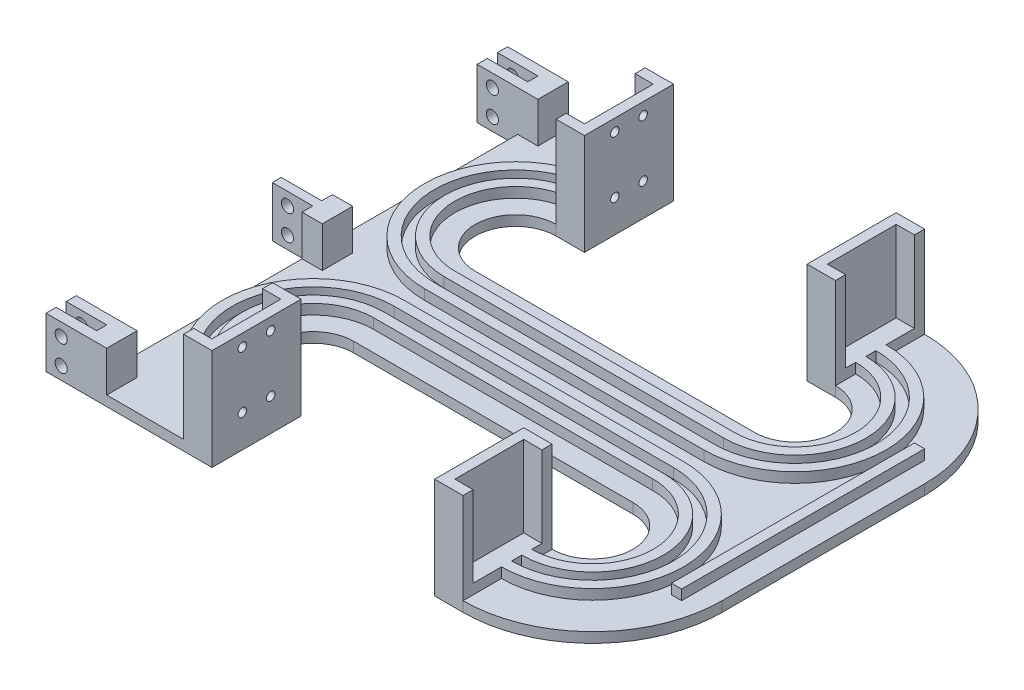
SolidWorks part; units mm, degrees
ref_plane "Front Plane" through (0, 0, 0) normal (0, 0, 1) x (1, 0, 0)
ref_plane "Top Plane" through (0, 0, 0) normal (0, 1, 0) x (1, 0, 0)
ref_plane "Right Plane" through (0, 0, 0) normal (1, 0, 0) x (0, 0, -1)
sketch "Sketch2" plane through (0, 0, 0) normal (0, 1, 0) x (1, 0, 0)
  line L0 (62.5, 25) -> (62.5, -25)
  line L1 (23.5, -35) -> (30.5, -35)
  line L2 (23.5, -57) -> (30.5, -57)
  line L3 (30.5, -15) -> (-38.5, -15)
  line L4 (-62.5, 0) -> (62.5, 0) construction
  line L5 (30.5, 57) -> (30.5, -57) construction
  line L6 (23.5, -35) -> (23.5, -57)
  line L7 (-31.5, -35) -> (-38.5, -35)
  line L8 (-31.5, -57) -> (-38.5, -57)
  line L9 (-38.5, -57) -> (-38.5, 57) construction
  line L10 (62.5, -25) -> (-62.5, -25) construction
  line L11 (-38.5, -57) -> (-62.5, -57)
  line L12 (-31.5, -35) -> (-31.5, -57)
  line L13 (-62.5, -57) -> (-62.5, 57)
  line L14 (62.5, 25) -> (-62.5, 25) construction
  line L15 (-31.5, 35) -> (-31.5, 57)
  line L16 (-38.5, 57) -> (-62.5, 57)
  line L17 (-31.5, 57) -> (-38.5, 57)
  line L18 (-31.5, 35) -> (-38.5, 35)
  line L19 (23.5, 35) -> (23.5, 57)
  line L20 (30.5, 15) -> (-38.5, 15)
  line L21 (23.5, 57) -> (30.5, 57)
  line L22 (23.5, 35) -> (30.5, 35)
  arc A0 (62.5, -25) -> (30.5, -57) centre (30.5, -25) cw
  arc A1 (30.5, -35) -> (30.5, -15) centre (30.5, -25) ccw
  arc A2 (-38.5, -15) -> (-38.5, -35) centre (-38.5, -25) ccw
  arc A3 (-38.5, 15) -> (-38.5, 35) centre (-38.5, 25) cw
  arc A4 (30.5, 35) -> (30.5, 15) centre (30.5, 25) cw
  arc A5 (62.5, 25) -> (30.5, 57) centre (30.5, 25) ccw
  point P33 (-38.5, 0)
  point P34 (30.5, 0)
  point P45 (0, 0)
  dimension "D2" = 10
  dimension "D1" = 25
  dimension "D3" = 125
  dimension "D4" = 55
  dimension "D5" = 22
  dimension "D6" = 7
extrude "Boss-Extrude1" add sketch "Sketch2" along normal blind 2.5
sketch "Sketch3" plane through (0, 2.5, 0) normal (0, 1, 0) x (1, 0, 0)
  line L0 (30.5, -40.0006) -> (30.5, -35)
  line L1 (30.3681, -7.5) -> (-38.6319, -7.5)
  line L3 (30.3681, -10) -> (-38.6319, -10)
  line L5 (0, 0) -> (62.5, 0) construction
  line L6 (62.5, -25) -> (62.5, 25) construction
  line L7 (-38.5, -15) -> (30.5, -15) construction
  line L8 (30.5, -2.5) -> (-38.5, -2.5)
  line L10 (30.5, -5) -> (-38.5, -5)
  line L12 (-38.5, -40.0006) -> (-38.5, -35)
  line L13 (-38.5, -35) -> (-31.5, -35)
  line L14 (-31.5, -35) -> (-31.5, -57)
  line L15 (-31.5, -57) -> (-38.5, -57)
  line L16 (-62.5, -57) -> (-31.5, -57) construction
  line L17 (-38.5, -57) -> (-38.5, -47.5)
  line L18 (-38.5, -42.5005) -> (-38.5, -45)
  line L19 (30.5, -35) -> (23.5, -35)
  line L20 (23.5, -35) -> (23.5, -57)
  line L21 (23.5, -57) -> (30.5, -57)
  line L22 (30.5, -57) -> (30.5, -47.5)
  line L23 (30.5, -42.5005) -> (30.5, -45)
  line L24 (30.5, 42.5005) -> (30.5, 45)
  line L25 (30.5, 57) -> (30.5, 47.5)
  line L26 (23.5, 57) -> (30.5, 57)
  line L27 (23.5, 35) -> (23.5, 57)
  line L28 (30.5, 35) -> (23.5, 35)
  line L29 (-38.5, 42.5005) -> (-38.5, 45)
  line L30 (-38.5, 57) -> (-38.5, 47.5)
  line L31 (-31.5, 57) -> (-38.5, 57)
  line L32 (-31.5, 35) -> (-31.5, 57)
  line L33 (-38.5, 35) -> (-31.5, 35)
  line L34 (-38.5, 40.0006) -> (-38.5, 35)
  line L35 (30.5, 5) -> (-38.5, 5)
  line L36 (30.5, 2.5) -> (-38.5, 2.5)
  line L37 (30.3681, 10) -> (-38.6319, 10)
  line L38 (30.3681, 7.5) -> (-38.6319, 7.5)
  line L39 (30.5, 40.0006) -> (30.5, 35)
  line L40 (57.5, 30) -> (55, 30)
  line L42 (57.5, 30) -> (57.5, -30)
  line L43 (57.5, -30) -> (55, -30)
  line L44 (55, 30) -> (55, -30)
  arc A0 (-38.6319, -10) -> (-38.5, -40.0006) centre (-38.5, -25) ccw
  arc A1 (-38.6319, -7.5) -> (-38.5, -42.5005) centre (-38.5, -25) ccw
  arc A2 (-38.5, -5) -> (-38.5, -45) centre (-38.5, -25) ccw
  arc A3 (-38.5, -2.5) -> (-38.5, -47.5) centre (-38.5, -25) ccw
  arc A4 (30.3681, -10) -> (30.5, -40.0006) centre (30.5, -25) cw
  arc A5 (30.3681, -7.5) -> (30.5, -42.5005) centre (30.5, -25) cw
  arc A6 (30.5, -5) -> (30.5, -45) centre (30.5, -25) cw
  arc A7 (30.5, -2.5) -> (30.5, -47.5) centre (30.5, -25) cw
  arc A8 (30.5, 2.5) -> (30.5, 47.5) centre (30.5, 25) ccw
  arc A9 (30.5, 5) -> (30.5, 45) centre (30.5, 25) ccw
  arc A10 (30.3681, 7.5) -> (30.5, 42.5005) centre (30.5, 25) ccw
  arc A11 (30.3681, 10) -> (30.5, 40.0006) centre (30.5, 25) ccw
  arc A12 (-38.5, 2.5) -> (-38.5, 47.5) centre (-38.5, 25) cw
  arc A13 (-38.5, 5) -> (-38.5, 45) centre (-38.5, 25) cw
  arc A14 (-38.6319, 7.5) -> (-38.5, 42.5005) centre (-38.5, 25) cw
  arc A15 (-38.6319, 10) -> (-38.5, 40.0006) centre (-38.5, 25) cw
  point P49 (55, 0)
  point P50 (57.5, 0)
  point P53 (-38.5, -43.7502)
  point P54 (30.5, -43.7502)
  dimension "D5" = 22.5
  dimension "D6" = 20
  dimension "D7" = 17.5005
  dimension "D1" = 2.5
  dimension "D2" = 2.5
  dimension "D3" = 5
  dimension "D4" = 2.5
  dimension "D8" = 2.5
  dimension "D9" = 30
  dimension "D10" = 5
extrude "Boss-Extrude4" add sketch "Sketch3" along normal blind 2.5
sketch "Sketch6" plane through (0, 5, 0) normal (0, 1, 0) x (1, 0, 0)
  line L0 (-38.5, -35) -> (-31.5, -35)
  line L1 (-31.5, -35) -> (-31.5, -57)
  line L2 (-31.5, -57) -> (-38.5, -57)
  line L3 (-38.5, -57) -> (-38.5, -54.5)
  line L4 (-38.5, -47.5) -> (-38.5, -57) construction
  line L5 (-38.5, -54.5) -> (-34, -54.5)
  line L6 (-34, -54.5) -> (-34, -37.5)
  line L7 (-34, -37.5) -> (-38.5, -37.5)
  line L8 (-38.5, -35) -> (-38.5, -40.0006) construction
  line L9 (-38.5, -37.5) -> (-38.5, -35)
  line L11 (30.5, -35) -> (23.5, -35)
  line L12 (23.5, -35) -> (23.5, -57)
  line L13 (23.5, -57) -> (30.5, -57)
  line L14 (30.5, -57) -> (30.5, -54.5)
  line L15 (30.5, -57) -> (30.5, -47.5) construction
  line L16 (30.5, -54.5) -> (26, -54.5)
  line L17 (26, -54.5) -> (26, -37.5)
  line L18 (26, -37.5) -> (30.5, -37.5)
  line L19 (30.5, -40.0006) -> (30.5, -35) construction
  line L20 (30.5, -37.5) -> (30.5, -35)
  line L21 (-1.375, 0) -> (1.375, 0) construction
  line L22 (30.5, 37.5) -> (30.5, 35)
  line L23 (26, 37.5) -> (30.5, 37.5)
  line L24 (26, 54.5) -> (26, 37.5)
  line L25 (30.5, 54.5) -> (26, 54.5)
  line L26 (30.5, 57) -> (30.5, 54.5)
  line L27 (23.5, 57) -> (30.5, 57)
  line L28 (23.5, 35) -> (23.5, 57)
  line L29 (30.5, 35) -> (23.5, 35)
  line L30 (-38.5, 37.5) -> (-38.5, 35)
  line L31 (-34, 37.5) -> (-38.5, 37.5)
  line L32 (-34, 54.5) -> (-34, 37.5)
  line L33 (-38.5, 54.5) -> (-34, 54.5)
  line L34 (-38.5, 57) -> (-38.5, 54.5)
  line L35 (-31.5, 57) -> (-38.5, 57)
  line L36 (-31.5, 35) -> (-31.5, 57)
  line L37 (-38.5, 35) -> (-31.5, 35)
  dimension "D1" = 2.5
  dimension "D2" = 2.5
  dimension "D3" = 2.5
extrude "Boss-Extrude5" add sketch "Sketch6" along normal blind 20
sketch "Sketch7" plane through (23.5, 0, 0) normal (-1, 0, 0) x (0, 0, 1)
  line L0 (37.5, 25) -> (54.5, 25) construction
  line L1 (57, 25) -> (57, 2.5) construction
  circle A0 centre (46, 13.75) radius 3.75
  point P4 (46, 25)
  point P7 (57, 13.75)
  dimension "D1" = 7.5
extrude "Boss-Extrude6" add sketch "Sketch7" along normal blind 5.5 contours A0
sketch "Sketch9" plane through (23.5, 0, 0) normal (-1, 0, 0) x (0, 0, 1)
  line L0 (-54.5, 25) -> (-37.5, 25) construction
  line L1 (-57, 25) -> (-57, 2.5) construction
  circle A0 centre (-46, 13.75) radius 3.75
  point P5 (-46, 25)
  point P8 (-57, 13.75)
  dimension "D1" = 7.5
extrude "Boss-Extrude7" add sketch "Sketch9" along normal blind 5.5
sketch "Sketch10" plane through (-31.5, 0, 0) normal (1, 0, 0) x (0, 0, -1)
  line L0 (-57, 12.5) -> (-35, 12.5) construction
  line L1 (-57, 25) -> (-57, 0) construction
  line L2 (-35, 25) -> (-35, 0) construction
  line L3 (-46, 25) -> (-46, 0) construction
  line L4 (-57, 25) -> (-35, 25) construction
  line L5 (-57, 0) -> (-35, 0) construction
  line L6 (-57, 15) -> (-35, 15) construction
  circle A0 centre (-42.5, 22) radius 1.05
  circle A1 centre (-49.5, 22) radius 1.05
  circle A4 centre (-49.5, 8) radius 1.05
  circle A5 centre (-42.5, 8) radius 1.05
  dimension "D3" = 2.1
  dimension "D1" = 2.5
  dimension "D2" = 3.5
  dimension "D4" = 7
extrude "Cut-Extrude1" cut sketch "Sketch10" against normal blind 2.5
sketch "Sketch12" plane through (-31.5, 0, 0) normal (1, 0, 0) x (0, 0, -1)
  line L0 (46, 25) -> (46, 0) construction
  line L1 (35, 25) -> (57, 25) construction
  line L2 (35, 0) -> (57, 0) construction
  line L3 (57, 12.5) -> (35, 12.5) construction
  line L4 (57, 25) -> (57, 0) construction
  line L5 (35, 25) -> (35, 0) construction
  line L6 (35, 15) -> (57, 15) construction
  circle A0 centre (49.5, 22) radius 1.05
  circle A1 centre (42.5, 22) radius 1.05
  circle A2 centre (42.5, 8) radius 1.05
  circle A3 centre (49.5, 8) radius 1.05
  dimension "D4" = 2.1
  dimension "D1" = 2.5
  dimension "D2" = 7
  dimension "D3" = 3.5
extrude "Cut-Extrude2" cut sketch "Sketch12" against normal blind 2.5
sketch "Sketch14" plane through (0, 2.5, 0) normal (0, 1, 0) x (1, 0, 0)
  line L0 (-62.5, 57) -> (-62.5, -57) construction
  line L1 (-62.5, 3.75) -> (-57.5, 3.75)
  line L2 (-62.5, 3.75) -> (-62.5, -3.75)
  line L3 (-62.5, -3.75) -> (-57.5, -3.75)
  line L4 (-57.5, 3.75) -> (-57.5, -3.75)
  line L6 (-62.5, -57) -> (-57.5, -57)
  line L7 (-62.5, -57) -> (-62.5, -49.5)
  line L8 (-62.5, -49.5) -> (-57.5, -49.5)
  line L9 (-57.5, -57) -> (-57.5, -49.5)
  line L10 (-62.5, 57) -> (-57.5, 57)
  line L11 (-62.5, 57) -> (-62.5, 49.5)
  line L12 (-62.5, 49.5) -> (-57.5, 49.5)
  line L13 (-57.5, 57) -> (-57.5, 49.5)
  point P6 (-57.5, 0)
  dimension "D1" = 7.5
  dimension "D2" = 5
  dimension "D3" = 7.5
extrude "Boss-Extrude8" add sketch "Sketch14" along normal blind 10
sketch "Sketch15" plane through (-62.5, 0, 0) normal (-1, 0, 0) x (0, 0, 1)
  line L0 (-57, 0) -> (57, 0) construction
  line L5 (-1.1, 12.5) -> (1.1, 12.5)
  line L6 (57, 12.5) -> (54.5, 12.5)
  line L7 (57, 12.5) -> (57, 0)
  line L8 (57, 0) -> (54.5, 0)
  line L9 (54.5, 12.5) -> (54.5, 0)
  line L10 (49.5, 12.5) -> (52, 12.5)
  line L11 (49.5, 12.5) -> (49.5, 0)
  line L12 (49.5, 0) -> (52, 0)
  line L13 (52, 12.5) -> (52, 0)
  line L27 (-3.75, 12.5) -> (3.75, 12.5) construction
  line L28 (1.1, 12.5) -> (1.1, 0)
  line L29 (1.1, 0) -> (-1.1, 0)
  line L31 (0, 12.5) -> (0, 0) construction
  line L32 (-1.1, 12.5) -> (-1.1, 0)
  line L33 (-52, 12.5) -> (-52, 0)
  line L34 (-49.5, 0) -> (-52, 0)
  line L35 (-49.5, 12.5) -> (-49.5, 0)
  line L36 (-49.5, 12.5) -> (-52, 12.5)
  line L37 (-54.5, 12.5) -> (-54.5, 0)
  line L38 (-57, 0) -> (-54.5, 0)
  line L39 (-57, 12.5) -> (-57, 0)
  line L40 (-57, 12.5) -> (-54.5, 12.5)
  dimension "D1" = 1.1
extrude "Boss-Extrude9" add sketch "Sketch15" along normal blind 10
sketch "Sketch16" plane through (0, 0, 57) normal (0, 0, 1) x (1, 0, 0)
  line L0 (-65, 12.5) -> (-65, 6.25) construction
  line L1 (-72.5, 12.5) -> (-57.5, 12.5) construction
  line L2 (-72.5, 0) -> (-72.5, 12.5) construction
  line L3 (-65, 9.375) -> (-72.5, 9.375) construction
  line L4 (-72.5, 6.25) -> (-57.5, 6.25) construction
  line L5 (-57.5, 12.5) -> (-57.5, 2.5) construction
  circle A2 centre (-68.75, 9.375) radius 1.5
  circle A3 centre (-68.75, 3.125) radius 1.5
  point P6 (-72.5, 6.25)
  point P13 (-68.75, 9.375)
  dimension "D1" = 3
extrude "Cut-Extrude3" cut sketch "Sketch16" against normal blind 114
